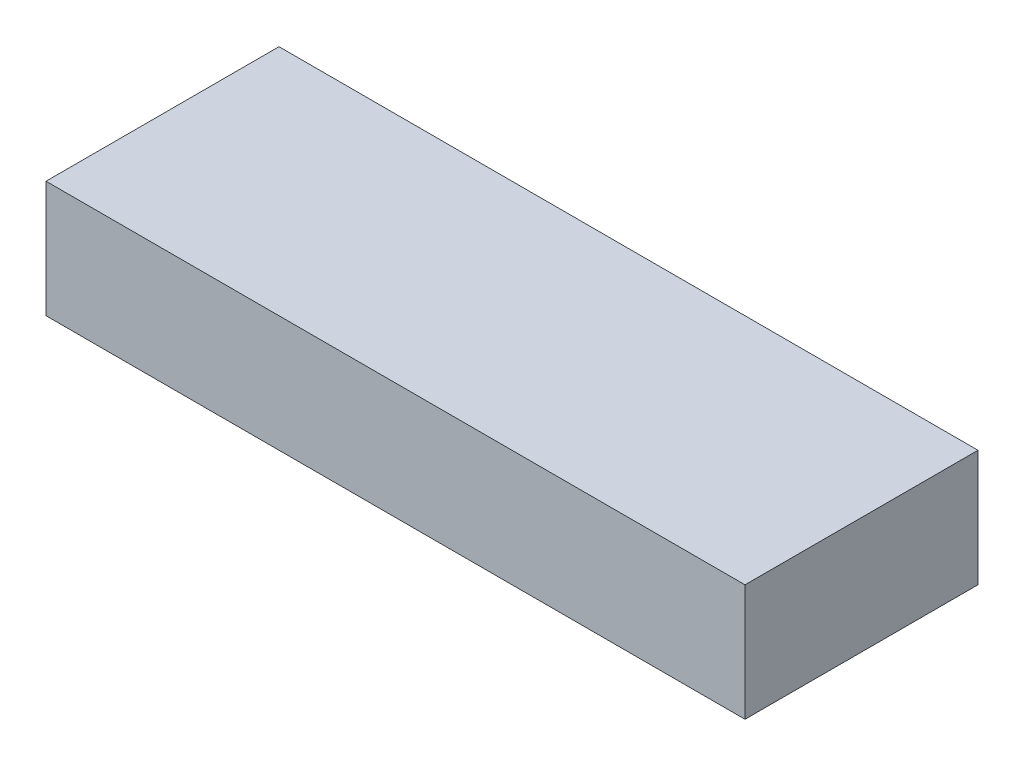
SolidWorks part; units mm, degrees
ref_plane "Front Plane" through (0, 0, 0) normal (0, 0, 1) x (1, 0, 0)
ref_plane "Top Plane" through (0, 0, 0) normal (0, 1, 0) x (1, 0, 0)
ref_plane "Right Plane" through (0, 0, 0) normal (1, 0, 0) x (0, 0, -1)
sketch "Sketch1" plane through (0, 0, 0) normal (0, 1, 0) x (1, 0, 0)
  line L1 (1500, -500) -> (-1500, -500)
  line L2 (1500, -500) -> (1500, 500)
  line L3 (1500, 500) -> (-1500, 500)
  line L4 (-1500, -500) -> (-1500, 500)
  line L5 (1500, -500) -> (-1500, 500) construction
  line L6 (1500, 500) -> (-1500, -500) construction
  point P0 (0, 0)
  dimension "D1" = 3000
  dimension "D2" = 1000
extrude "Boss-Extrude1" add sketch "Sketch1" along normal blind 500 contours L1 L4 L3 L2
